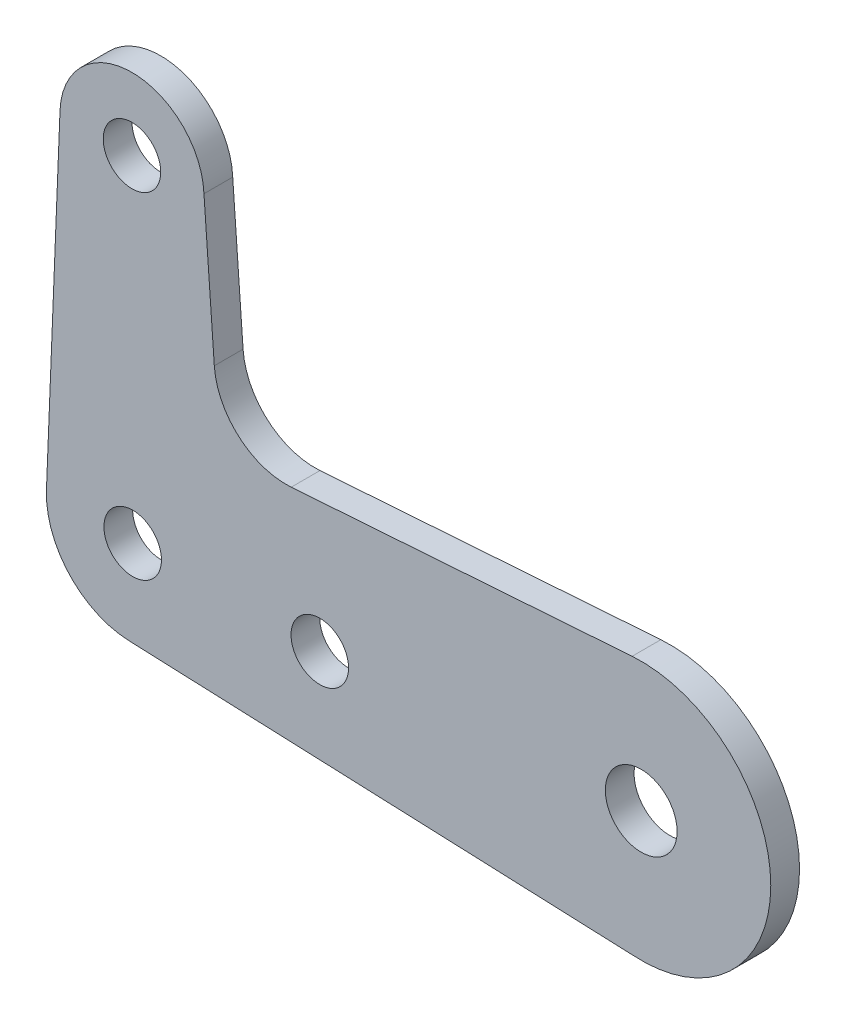
SolidWorks part; units mm, degrees
ref_plane "Front Plane" through (0, 0, 0) normal (0, 0, 1) x (1, 0, 0)
ref_plane "Top Plane" through (0, 0, 0) normal (0, 1, 0) x (1, 0, 0)
ref_plane "Right Plane" through (0, 0, 0) normal (1, 0, 0) x (0, 0, -1)
sketch "Sketch1" plane through (0, 0, 0) normal (0, 0, 1) x (1, 0, 0)
  line L0 (-8.5978, 31.3015) -> (-10.0935, -5.6633)
  line L1 (-0.9614, -15.5656) -> (54.5454, -17.8116)
  line L2 (8.4325, 15.4295) -> (7.2896, 31.3015)
  line L3 (16.9204, 8.0699) -> (54.5454, 10.7182)
  arc A0 (54.5454, 10.7182) -> (54.5454, -17.8116) centre (55.5495, -3.5467) cw
  arc A1 (-8.5978, 31.3015) -> (7.2896, 31.3015) centre (-0.6541, 30.98) cw
  arc A2 (-10.0935, -5.6633) -> (-0.9614, -15.5656) centre (-0.5763, -6.0484) ccw
  arc A3 (8.4325, 15.4295) -> (16.9204, 8.0699) centre (16.3622, 16.0005) ccw
  point P10 (-10.4786, -15.1805)
  dimension "D3" = 14.3002
  dimension "D4" = 7.9502
  dimension "D5" = 9.525
  dimension "D6" = 7.9502
  dimension "D1" = 46.482
  dimension "D2" = 65.024
extrude "Boss-Extrude1" add sketch "Sketch1" along normal blind 3.175
sketch "Sketch2" plane through (0, 0, 3.175) normal (0, 0, 1) x (1, 0, 0)
  circle A0 centre (-0.6541, 30.98) radius 3.175
  circle A2 centre (-0.5763, -6.0484) radius 3.175
  circle A3 centre (20.0739, -6.0484) radius 3.175
  circle A4 centre (55.5495, -3.5467) radius 3.9624
  dimension "D1" = 6.35
  dimension "D2" = 7.9248
  dimension "D3" = 20.6502
extrude "Cut-Extrude1" cut sketch "Sketch2" against normal through all
